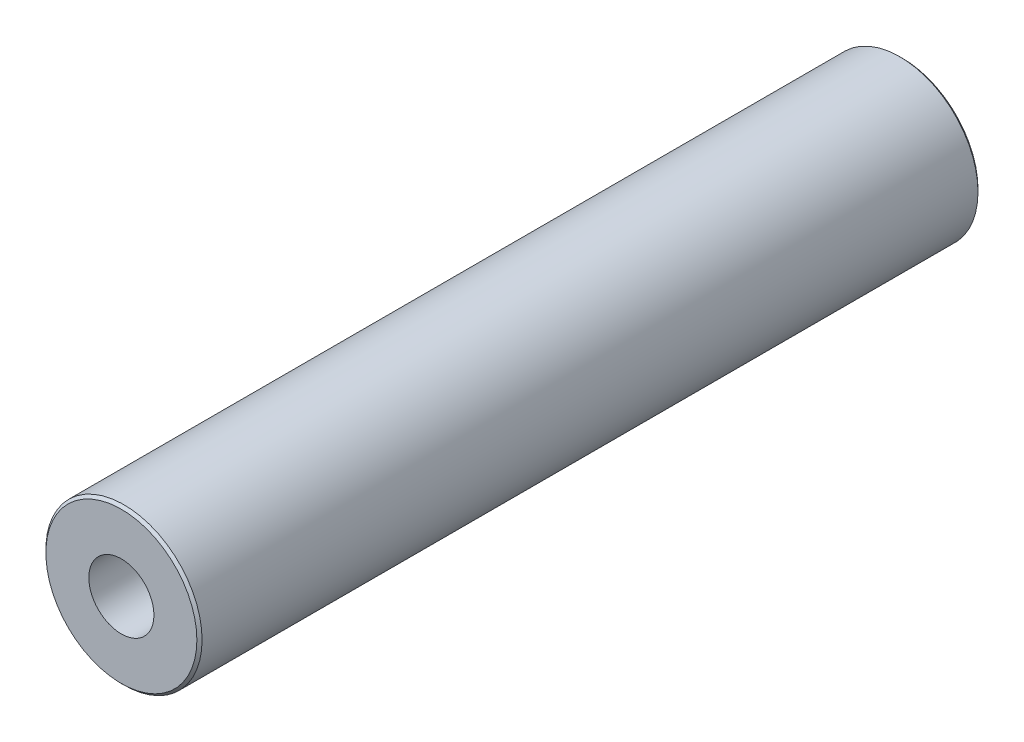
SolidWorks part; units mm, degrees
material "铸造不锈钢"
ref_plane "前视基准面" through (0, 0, 0) normal (0, 0, 1) x (1, 0, 0)
ref_plane "上视基准面" through (0, 0, 0) normal (0, 1, 0) x (1, 0, 0)
ref_plane "右视基准面" through (0, 0, 0) normal (1, 0, 0) x (0, 0, -1)
sketch "草图1" plane through (0, 0, 0) normal (0, 0, 1) x (1, 0, 0)
  circle A0 centre (0, 0) radius 3
  dimension "D1" = 6
extrude "凸台-拉伸1" add sketch "草图1" along normal mid plane 30
chamfer "倒角1" distance 0.1 angle 45 2 edges at (3, 0, -15) (3, 0, 15)
hole_wizard "M3 螺纹孔1" positions "草图2" profile "草图3" tap size "M3" standard "GB" end condition through all
sketch "草图2" plane through (0, 0, 15) normal (0, 0, 1) x (1, 0, 0)
  point P0 (0, 0)
sketch "草图3" plane through (0, 0, 15) normal (1, 0, 0) x (0, -1, 0)
  line L0 (0, 0) -> (0, 30)
  line L1 (0, 30) -> (1.25, 30)
  line L2 (1.25, 30) -> (1.25, 0)
  line L5 (1.25, 0) -> (0, 0)
  line L11 (0, -6.35) -> (0, 107.95) construction
  dimension "通孔螺纹孔钻头直径" = 2.5
  dimension "通孔螺纹孔钻头深度" = 30
cosmetic thread "孔螺蚊线1"
